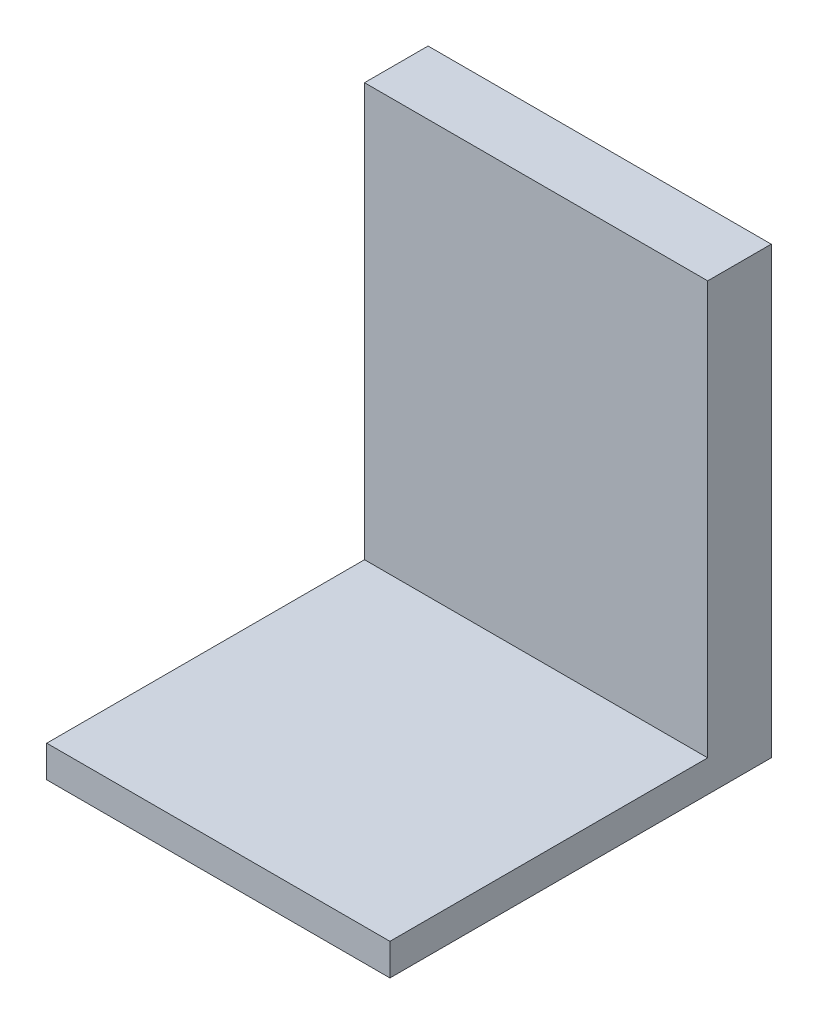
SolidWorks part; units mm, degrees
ref_plane "정면" through (0, 0, 0) normal (0, 0, 1) x (1, 0, 0)
ref_plane "윗면" through (0, 0, 0) normal (0, 1, 0) x (1, 0, 0)
ref_plane "우측면" through (0, 0, 0) normal (1, 0, 0) x (0, 0, -1)
sketch "Sketch1" plane through (0, 0, 0) normal (0, 1, 0) x (1, 0, 0)
  line L1 (0, 0) -> (670, 0)
  line L2 (0, 0) -> (0, 120)
  line L3 (0, 120) -> (670, 120)
  line L4 (670, 0) -> (670, 120)
  dimension "700" = 670
  dimension "D2" = 120
extrude "Boss-Extrude1" add sketch "Sketch1" along normal blind 530
sketch "Sketch2" plane through (0, 0, 0) normal (0, 0, 1) x (1, 0, 0)
  line L0 (0, 530) -> (0, 0) construction
  line L1 (10, 280) -> (110, 280)
  line L2 (10, 280) -> (10, 480)
  line L3 (10, 480) -> (110, 480)
  line L4 (110, 280) -> (110, 480)
  line L5 (0, 0) -> (670, 0) construction
  line L6 (120, 280) -> (120, 480)
  line L7 (120, 280) -> (220, 280)
  line L8 (220, 280) -> (220, 480)
  line L9 (120, 480) -> (220, 480)
  line L10 (230, 280) -> (230, 480)
  line L11 (230, 280) -> (330, 280)
  line L12 (330, 280) -> (330, 480)
  line L13 (230, 480) -> (330, 480)
  line L14 (340, 280) -> (340, 480)
  line L15 (340, 280) -> (440, 280)
  line L16 (440, 280) -> (440, 480)
  line L17 (340, 480) -> (440, 480)
  line L18 (450, 280) -> (450, 480)
  line L19 (450, 280) -> (550, 280)
  line L20 (550, 280) -> (550, 480)
  line L21 (450, 480) -> (550, 480)
  line L22 (560, 280) -> (560, 480)
  line L23 (560, 280) -> (660, 280)
  line L24 (660, 280) -> (660, 480)
  line L25 (560, 480) -> (660, 480)
  line L27 (10, 10) -> (660, 10)
  line L28 (10, 10) -> (10, 260)
  line L29 (10, 260) -> (660, 260)
  line L30 (660, 10) -> (660, 260)
  line L31 (0, 530) -> (670, 530) construction
  point P6 (10, 380)
  dimension "D1" = 100
  dimension "D2" = 200
  dimension "D3" = 10
  dimension "D4" = 50
  dimension "D6" = 10
  dimension "D7" = 20
  dimension "D5" = 6
extrude "Cut-Extrude1" cut sketch "Sketch2" against normal blind 100
sketch "Sketch3" plane through (0, 530, 0) normal (0, 1, 0) x (1, 0, 0)
  line L1 (670, 120) -> (0, 120) construction
  line L2 (0, 120) -> (0, 0) construction
  circle A0 centre (60, 60) radius 50
  circle A1 centre (170, 60) radius 50
  circle A2 centre (280, 60) radius 50
  circle A3 centre (390, 60) radius 50
  circle A4 centre (500, 60) radius 50
  circle A5 centre (610, 60) radius 50
  dimension "D1" = 100
  dimension "D2" = 10
  dimension "D3" = 10
  dimension "D4" = 6
extrude "Cut-Extrude2" cut sketch "Sketch3" against normal blind 260
hole_wizard "Ø12.0 (12) Diameter Hole2" positions "3DSketch1" profile "Sketch7" hole size "Ø12.0" standard "Ansi Metric"
sketch3d "3DSketch1"
  point P0 (59.7046, 270, -102.4117)
  point P2 (171.5567, 270, -102.6076)
  point P4 (280.8723, 270, -102.3969)
  point P6 (391.0687, 270, -102.7535)
  point P8 (500.7133, 270, -101.754)
  point P10 (609.5165, 270, -101.1227)
sketch "Sketch7" plane through (59.7046, 270, -102.4117) normal (1, 0, 0) x (0, 0, 1)
  line L0 (0, 0) -> (0, 33.6052)
  line L1 (0, 33.6052) -> (6, 30)
  line L2 (6, 30) -> (6, 0)
  line L5 (6, 0) -> (0, 0)
  line L10 (0, 33.6052) -> (-6, 30) construction
  line L11 (0, -6.35) -> (0, 107.95) construction
  dimension "구멍 지름" = 12
  dimension "구멍 깊이" = 30
  dimension "드릴 각도" = 118
sketch "Sketch8" plane through (0, 0, 0) normal (0, 0, 1) x (1, 0, 0)
  line L0 (660, 280) -> (660, 480) construction
  line L1 (10, 280) -> (660, 280)
  line L2 (10, 280) -> (10, 330)
  line L3 (10, 330) -> (660, 330)
  line L4 (660, 280) -> (660, 330)
  dimension "D1" = 50
extrude "Boss-Extrude2" add sketch "Sketch8" against normal blind 5
sketch "Sketch9" plane through (670, 0, 0) normal (1, 0, 0) x (0, 0, -1)
  line L0 (0, 530) -> (0, 0) construction
  line L1 (10, 10) -> (20, 10)
  line L2 (10, 10) -> (10, 260)
  line L3 (10, 260) -> (20, 260)
  line L4 (20, 10) -> (20, 260)
  line L5 (0, 0) -> (120, 0) construction
  dimension "D1" = 10
  dimension "D2" = 10
  dimension "D3" = 10
  dimension "D4" = 250
extrude "Cut-Extrude3" cut sketch "Sketch9" against normal blind 717
sketch "Sketch10" plane through (0, 10, 0) normal (0, 1, 0) x (1, 0, 0)
  line L0 (670, 120) -> (0, 120) construction
  line L1 (365, 61.9436) -> (350, 87.9243)
  line L2 (350, 87.9243) -> (320, 87.9243)
  line L3 (320, 87.9243) -> (305, 61.9436)
  line L4 (305, 61.9436) -> (320, 35.9628)
  line L5 (320, 35.9628) -> (350, 35.9628)
  line L6 (350, 35.9628) -> (365, 61.9436)
  line L7 (0, 120) -> (0, 0) construction
  circle A0 centre (335, 61.9436) radius 25.9808 construction
  dimension "D1" = 60
  dimension "D2" = 305
extrude "Cut-Extrude4" cut sketch "Sketch10" against normal blind 5
sketch "Sketch11" plane through (0, 0, -100) normal (0, 0, 1) x (1, 0, 0)
  line L0 (10, 10) -> (660, 10) construction
  line L1 (250, 10) -> (260, 10)
  line L2 (250, 10) -> (250, 110)
  line L3 (250, 110) -> (260, 110)
  line L4 (260, 10) -> (260, 110)
  line L5 (660, 10) -> (660, 260) construction
  line L6 (410, 10) -> (420, 10)
  line L7 (410, 10) -> (410, 110)
  line L8 (410, 110) -> (420, 110)
  line L9 (420, 10) -> (420, 110)
  line L10 (25, 198.4569) -> (325, 145.5588)
  line L11 (325, 145.5588) -> (325, 122.0178)
  line L12 (325, 122.0178) -> (345, 122.0178)
  line L13 (345, 122.0178) -> (345, 145.5588)
  line L14 (345, 145.5588) -> (645, 198.4569)
  line L15 (645, 198.4569) -> (25, 198.4569)
  point P18 (345, 133.7883)
  dimension "D1" = 10
  dimension "D2" = 10
  dimension "D3" = 100
  dimension "D4" = 100
  dimension "D5" = 150
  dimension "D6" = 240
  dimension "D7" = 20
  dimension "D8" = 65
  dimension "D9" = 100
  dimension "D10" = 620
  dimension "D11" = 100
extrude "Boss-Extrude3" add sketch "Sketch11" along normal blind 78 separate body
sketch "Sketch12" plane through (0, 0, -100) normal (0, 0, 1) x (1, 0, 0)
  line L0 (660, 260) -> (10, 260) construction
  line L1 (75.1986, 260) -> (95.1986, 260)
  line L2 (75.1986, 260) -> (75.1986, 230)
  line L3 (75.1986, 230) -> (95.1986, 230)
  line L4 (95.1986, 260) -> (95.1986, 230)
  line L5 (65.1986, 260) -> (65.1986, 240) construction
  line L6 (185.1986, 260) -> (185.1986, 230)
  line L7 (185.1986, 260) -> (205.1986, 260)
  line L8 (205.1986, 260) -> (205.1986, 230)
  line L9 (185.1986, 230) -> (205.1986, 230)
  line L10 (295.1986, 260) -> (295.1986, 230)
  line L11 (295.1986, 260) -> (315.1986, 260)
  line L12 (315.1986, 260) -> (315.1986, 230)
  line L13 (295.1986, 230) -> (315.1986, 230)
  line L14 (405.1986, 260) -> (405.1986, 230)
  line L15 (405.1986, 260) -> (425.1986, 260)
  line L16 (425.1986, 260) -> (425.1986, 230)
  line L17 (405.1986, 230) -> (425.1986, 230)
  line L18 (515.1986, 260) -> (515.1986, 230)
  line L19 (515.1986, 260) -> (535.1986, 260)
  line L20 (535.1986, 260) -> (535.1986, 230)
  line L21 (515.1986, 230) -> (535.1986, 230)
  line L22 (625.1986, 260) -> (625.1986, 230)
  line L23 (625.1986, 260) -> (645.1986, 260)
  line L24 (645.1986, 260) -> (645.1986, 230)
  line L25 (625.1986, 230) -> (645.1986, 230)
  dimension "D1" = 20
  dimension "D2" = 30
  dimension "D3" = 10
  dimension "D4" = 6
extrude "Cut-Extrude5" cut sketch "Sketch12" against normal blind 80
sketch "Sketch15" plane through (345, 0, 0) normal (1, 0, 0) x (0, 0, -1)
  line L0 (20, 10) -> (20, 260) construction
  line L1 (20, 121.4638) -> (50, 121.4638)
  line L2 (20, 121.4638) -> (20, 145)
  line L3 (20, 145) -> (50, 145)
  line L4 (50, 121.4638) -> (50, 145)
  line L5 (120, 530) -> (120, 0) construction
  line L6 (100, 116.0134) -> (70, 116.0134)
  line L7 (100, 116.0134) -> (100, 145)
  line L8 (100, 145) -> (70, 145)
  line L9 (70, 116.0134) -> (70, 145)
  line L10 (20, 260) -> (10, 260) construction
  dimension "D1" = 20
  dimension "D2" = 20
  dimension "D3" = 115
  dimension "D4" = 30
extrude "Cut-Extrude7" cut sketch "Sketch15" against normal blind 35
shell "Shell1" thickness 3
sketch "Sketch16" plane through (0, 122.0178, 0) normal (0, -1, 0) x (1, 0, 0)
  line L0 (345, -50) -> (325, -50) construction
  line L1 (328, -53) -> (342, -53)
  line L2 (328, -53) -> (328, -67)
  line L3 (328, -67) -> (342, -67)
  line L4 (342, -53) -> (342, -67)
  line L5 (325, -50) -> (325, -70) construction
  line L6 (345, -50) -> (345, -70) construction
  line L7 (325, -70) -> (345, -70) construction
  dimension "D1" = 3
  dimension "D2" = 3
  dimension "D3" = 3
  dimension "D4" = 3
extrude "Cut-Extrude8" cut sketch "Sketch16" against normal blind 35
sketch "Sketch17" plane through (0, 0, 0) normal (0, 0, 1) x (1, 0, 0)
  text T0 "<b>DIFF_USER</b>" font "Britannic Bold" height in points 72
extrude "Boss-Extrude4" add sketch "Sketch17" along normal blind 5
sketch "Sketch18" plane through (0, 0, 0) normal (0, 0, 1) x (1, 0, 0)
  line L0 (0, 530) -> (670, 530) construction
  line L1 (0, 530) -> (670, 530)
  line L2 (0, 530) -> (0, 280)
  line L3 (0, 280) -> (670, 280)
  line L4 (670, 530) -> (670, 280)
  line L5 (670, 530) -> (670, 0) construction
  line L6 (0, 0) -> (670, 0) construction
  dimension "D1" = 280
extrude "Cut-Extrude10" cut sketch "Sketch18" against normal through all both and the other way through all
delete or keep bodies "Body-Delete/Keep 1" type delete bodies bodies 112
delete or keep bodies "Body-Delete/Keep 2" type delete bodies bodies 109
delete or keep bodies "Body-Delete/Keep 3" type delete bodies bodies 115
sketch "Sketch19" plane through (0, 0, -100) normal (0, 0, 1) x (1, 0, 0)
  line L0 (670, 280) -> (0, 280) construction
  line L6 (670, 0) -> (230, 0)
  line L7 (670, 0) -> (670, 280)
  line L8 (670, 280) -> (230, 280)
  line L9 (230, 0) -> (230, 280)
extrude "Cut-Extrude12" cut sketch "Sketch19" against normal through all both and the other way through all
sketch "Sketch20" plane through (0, 0, -120) normal (0, 0, -1) x (-1, 0, 0)
  line L0 (-230, 0) -> (0, 0) construction
  line L1 (-122, 0) -> (88.9189, 0)
  line L2 (-122, 0) -> (-122, 296.401)
  line L3 (-122, 296.401) -> (88.9189, 296.401)
  line L4 (88.9189, 0) -> (88.9189, 296.401)
  line L5 (-230, 280) -> (-230, 0) construction
  dimension "D1" = 108
extrude "Cut-Extrude14" cut sketch "Sketch20" against normal blind 156
sketch "Sketch21" plane through (0, 0, -100) normal (0, 0, 1) x (1, 0, 0)
  line L0 (230, 10) -> (230, 260) construction
  line L1 (122, 280) -> (230, 280)
  line L2 (122, 280) -> (122, 140)
  line L3 (122, 140) -> (230, 140)
  line L4 (230, 280) -> (230, 140)
  dimension "D1" = 140
extrude "Cut-Extrude15" cut sketch "Sketch21" against normal through all both and the other way through all
